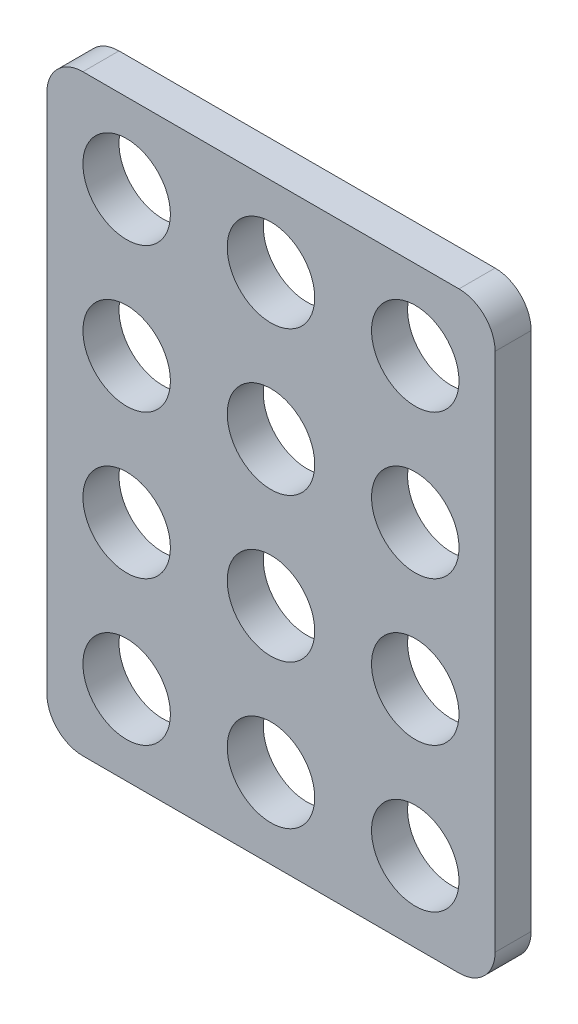
SolidWorks part; units mm, degrees
ref_plane "Front Plane" through (0, 0, 0) normal (0, 0, 1) x (1, 0, 0)
ref_plane "Top Plane" through (0, 0, 0) normal (0, 1, 0) x (1, 0, 0)
ref_plane "Right Plane" through (0, 0, 0) normal (1, 0, 0) x (0, 0, -1)
sketch "Sketch1" plane through (0, 0, 0) normal (0, 0, 1) x (1, 0, 0)
  line L1 (2, 0) -> (22.85, 0)
  line L2 (0, 2) -> (0, 30.85)
  line L3 (2, 32.85) -> (22.85, 32.85)
  line L4 (24.85, 2) -> (24.85, 30.85)
  arc A0 (22.85, 0) -> (24.85, 2) centre (22.85, 2) ccw
  arc A1 (2, 0) -> (0, 2) centre (2, 2) cw
  arc A2 (0, 30.85) -> (2, 32.85) centre (2, 30.85) cw
  arc A3 (22.85, 32.85) -> (24.85, 30.85) centre (22.85, 30.85) cw
  point P7 (24.85, 0)
  point P10 (0, 0)
  point P15 (24.85, 32.85)
  dimension "D3" = 2
  dimension "D4" = 2
  dimension "D5" = 2
  dimension "D6" = 2
  dimension "D1" = 24.85
  dimension "D2" = 32.85
extrude "Boss-Extrude2" add sketch "Sketch1" along normal blind 2
sketch "Sketch2" plane through (0, 0, 2) normal (0, 0, 1) x (1, 0, 0)
  line L1 (0, 30.85) -> (0, 2) construction
  line L2 (24.85, 2) -> (24.85, 30.85) construction
  line L4 (2, 0) -> (22.85, 0) construction
  circle A0 centre (4.425, 4.425) radius 2.425
  circle A1 centre (12.425, 4.425) radius 2.425
  circle A2 centre (20.425, 4.425) radius 2.425
  circle A3 centre (4.425, 12.425) radius 2.425
  circle A4 centre (12.425, 12.425) radius 2.425
  circle A5 centre (20.425, 12.425) radius 2.425
  circle A6 centre (4.425, 20.425) radius 2.425
  circle A7 centre (12.425, 20.425) radius 2.425
  circle A8 centre (20.425, 20.425) radius 2.425
  circle A12 centre (4.425, 28.425) radius 2.425
  circle A13 centre (12.425, 28.425) radius 2.425
  circle A14 centre (20.425, 28.425) radius 2.425
  dimension "D1" = 4.85
  dimension "D2" = 4.85
  dimension "D3" = 4.85
  dimension "D4" = 3.15
  dimension "D5" = 3.15
  dimension "D6" = 2
  dimension "D7" = 2
  dimension "D8" = 2
  dimension "D9" = 2
  dimension "D10" = 3.15
  dimension "D11" = 3.15
  dimension "D12" = 3.15
  dimension "D13" = 4.85
  dimension "D14" = 4.85
  dimension "D15" = 4.85
  dimension "D16" = 4.85
  dimension "D17" = 4.85
  dimension "D18" = 4.85
  dimension "D19" = 4.85
  dimension "D20" = 4.85
  dimension "D21" = 4.85
  dimension "D22" = 3.15
  dimension "D23" = 3.15
  dimension "D24" = 2
  dimension "D25" = 3.15
  dimension "D26" = 3.15
  dimension "D27" = 3.15
  dimension "D28" = 3.15
  dimension "D29" = 3.15
  dimension "D30" = 3.15
  dimension "D31" = 2
  dimension "D32" = 3.15
  dimension "D33" = 3.15
  dimension "D34" = 2
  dimension "D35" = 3.15
  dimension "D36" = 3.15
extrude "Cut-Extrude1" cut sketch "Sketch2" against normal blind 2
